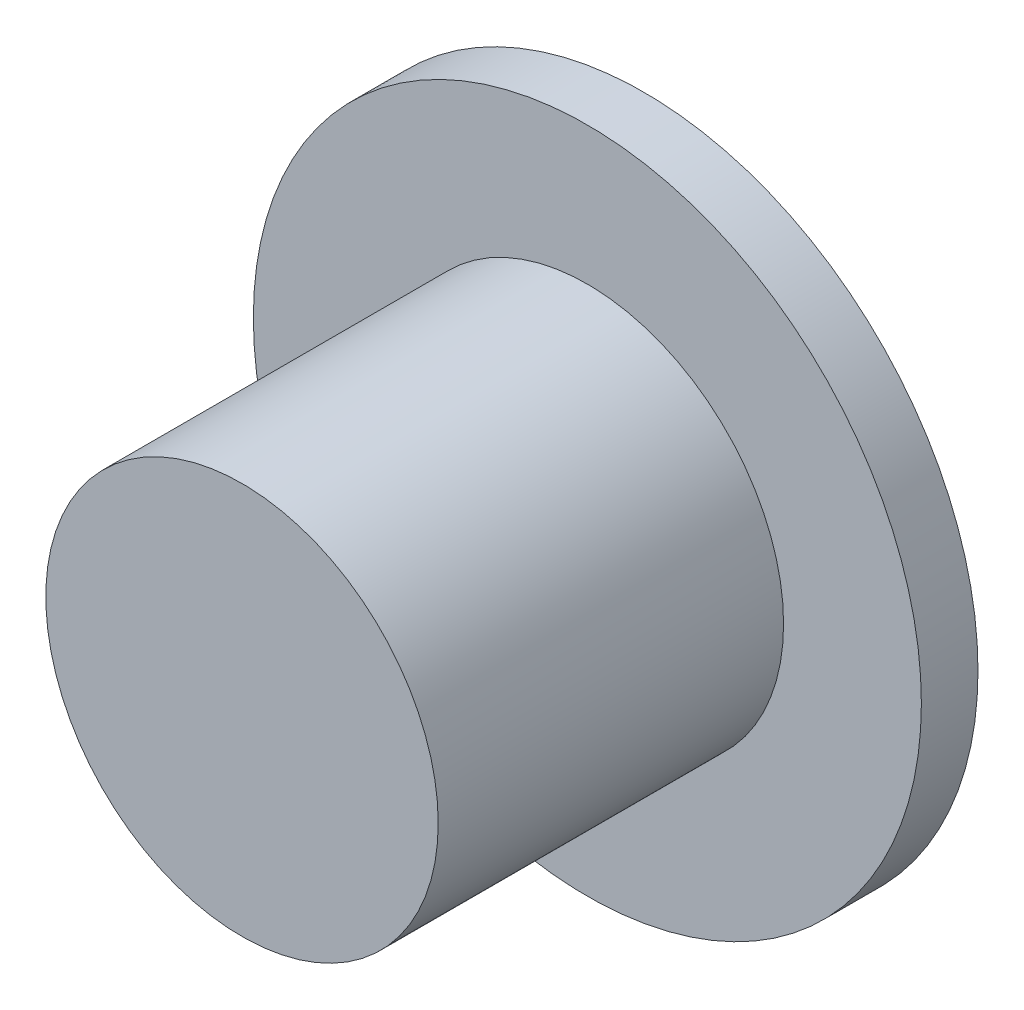
SolidWorks part; units mm, degrees
ref_plane "Front" through (0, 0, 0) normal (0, 0, 1) x (1, 0, 0)
ref_plane "Top" through (0, 0, 0) normal (0, 1, 0) x (1, 0, 0)
ref_plane "Right" through (0, 0, 0) normal (1, 0, 0) x (0, 0, -1)
other "Configuration Table"
sketch "Sketch1" plane through (0, 0, 0) normal (0, 0, 1) x (1, 0, 0)
  circle A0 centre (0, 0) radius 58.9984
extrude "Boss-Extrude1" add sketch "Sketch1" along normal blind 10
sketch "Sketch2" plane through (0, 0, 10) normal (0, 0, 1) x (1, 0, 0)
  circle A0 centre (0, 0) radius 34.6578
extrude "Boss-Extrude2" add sketch "Sketch2" along normal blind 61
